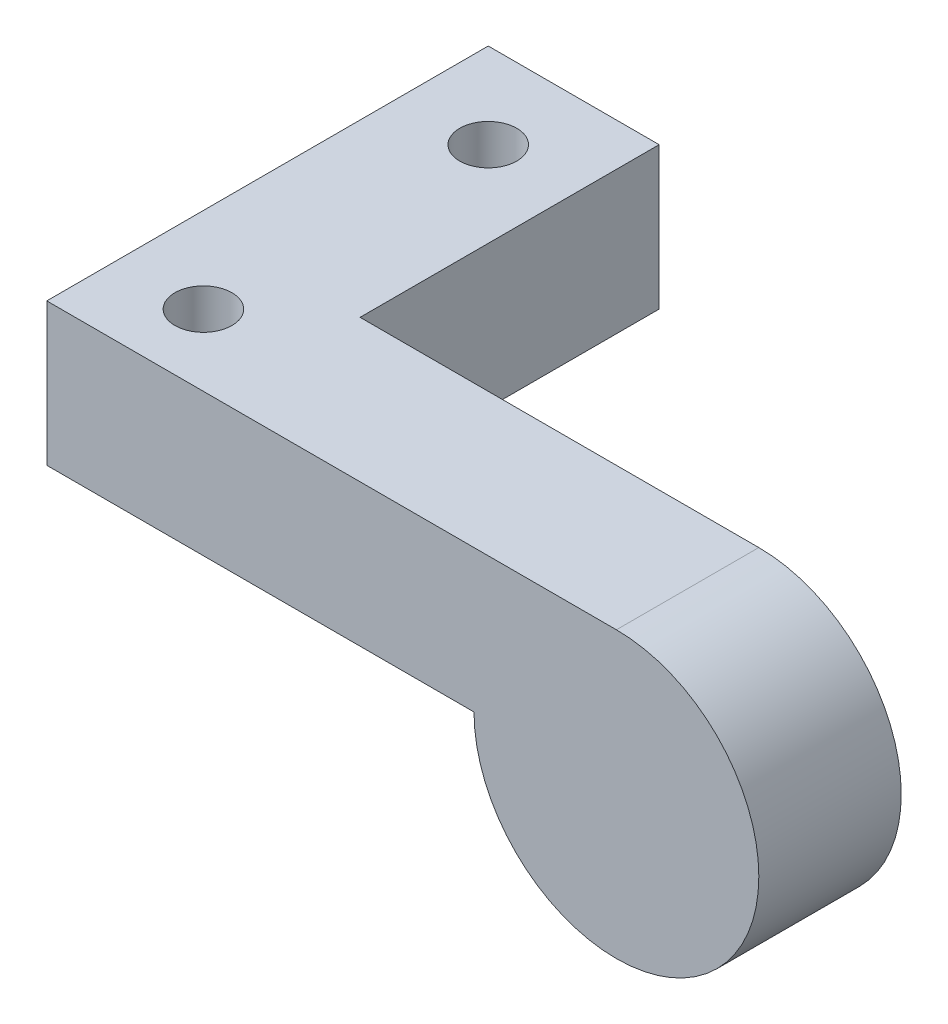
SolidWorks part; units mm, degrees
ref_plane "前视基准面" through (0, 0, 0) normal (0, 0, 1) x (1, 0, 0)
ref_plane "上视基准面" through (0, 0, 0) normal (0, 1, 0) x (1, 0, 0)
ref_plane "右视基准面" through (0, 0, 0) normal (1, 0, 0) x (0, 0, -1)
other "Configuration Table"
sketch "草图1" plane through (0, 0, 0) normal (0, 0, 1) x (1, 0, 0)
  circle A0 centre (0, 0) radius 2.5
  circle A1 centre (0, 0) radius 5
  dimension "D1" = 5
  dimension "D2" = 10
extrude "凸台-拉伸1" add sketch "草图1" along normal blind 3
sketch "草图2" plane through (0, 0, 3) normal (0, 0, 1) x (1, 0, 0)
  circle A0 centre (0, 0) radius 5
  dimension "D1" = 10
extrude "凸台-拉伸2" add sketch "草图2" along normal blind 2
sketch "草图3" plane through (0, 0, 0) normal (0, 0, -1) x (-1, 0, 0)
  line L0 (0, 5) -> (20, 5)
  line L1 (20, 5) -> (20, -5)
  line L2 (20, -5) -> (0, -5)
  arc A0 (0, 5) -> (0, -5) centre (0, 0) cw
  circle A1 centre (0, 0) radius 5 construction
  dimension "D1" = 20
extrude "凸台-拉伸3" add sketch "草图3" against normal blind 5
sketch "草图6" plane through (0, 5, 0) normal (0, 1, 0) x (1, 0, 0)
  line L0 (-30, -2.5) -> (49970, -2.5) construction
  line L1 (-20, -5) -> (-20, 0) construction
  circle A0 centre (-17, -2.5) radius 1
  point P4 (-20, -2.5)
  dimension "D1" = 2
  dimension "D2" = 3
extrude "切除-拉伸2" cut sketch "草图6" against normal blind 10
sketch "草图7" plane through (0, 0, 0) normal (0, 0, -1) x (-1, 0, 0)
  line L0 (0, -5) -> (20, -5) construction
  line L1 (20, 5) -> (14, 5)
  line L2 (20, 5) -> (20, -5)
  line L3 (20, -5) -> (14, -5)
  line L4 (14, 5) -> (14, -5)
  dimension "D1" = 6
extrude "凸台-拉伸5" add sketch "草图7" along normal blind 10.5
sketch "草图8" plane through (0, 5, 0) normal (0, 1, 0) x (1, 0, 0)
  line L0 (-20, 10.5) -> (-14, 10.5) construction
  circle A0 centre (-17, 7.5) radius 1
  dimension "D1" = 2
  dimension "D2" = 3
extrude "切除-拉伸3" cut sketch "草图8" against normal blind 12
sketch "草图9" plane through (0, 0, 0) normal (0, 0, -1) x (-1, 0, 0)
  line L0 (5, 0) -> (20, 0)
  line L1 (20, -5) -> (20, 5) construction
  line L2 (20, 0) -> (20, -5)
  line L3 (20, -5) -> (0, -5)
  arc A0 (0, -5) -> (5, 0) centre (0, 0) ccw
extrude "切除-拉伸4" cut sketch "草图9" against normal through all both and the other way through all
